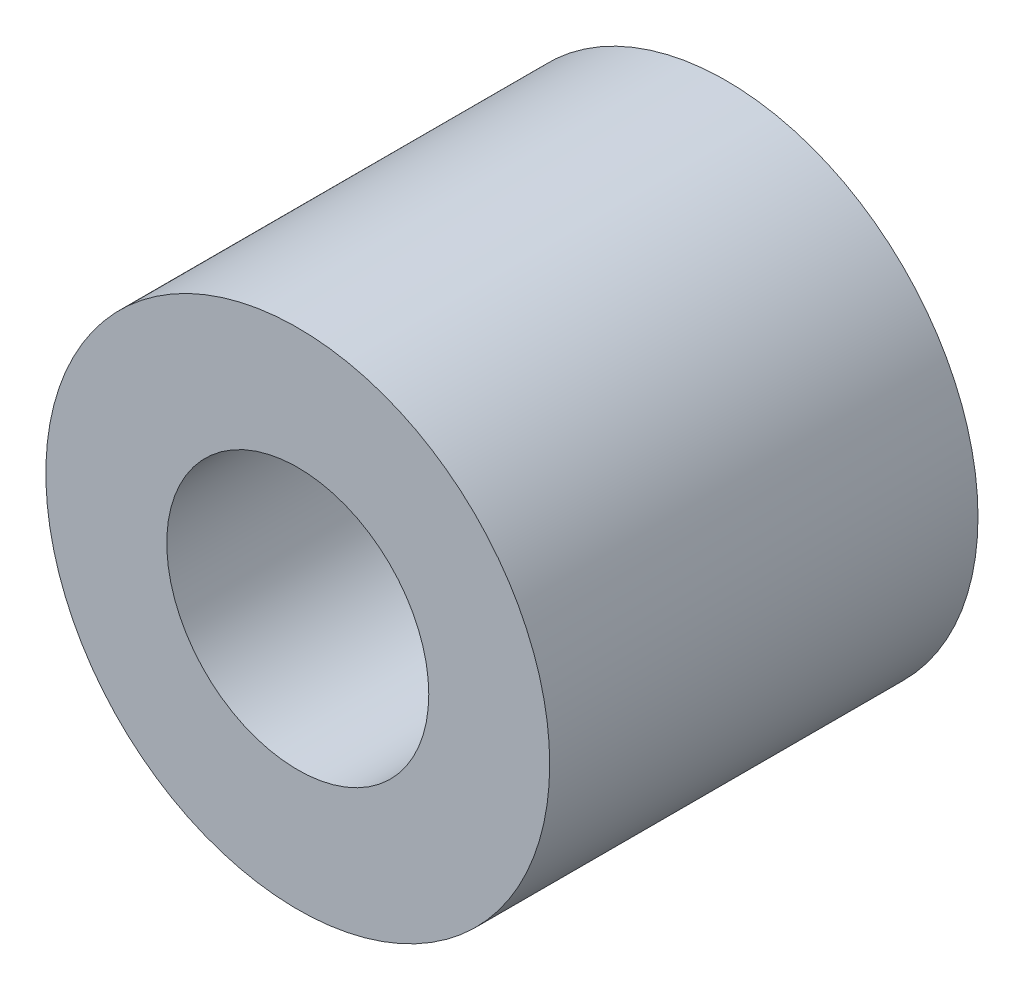
SolidWorks part; units mm, degrees
ref_plane "前视基准面" through (0, 0, 0) normal (0, 0, 1) x (1, 0, 0)
ref_plane "上视基准面" through (0, 0, 0) normal (0, 1, 0) x (1, 0, 0)
ref_plane "右视基准面" through (0, 0, 0) normal (1, 0, 0) x (0, 0, -1)
sketch "草图1" plane through (0, 0, 0) normal (0, 0, 1) x (1, 0, 0)
  circle A0 centre (0, 0) radius 2.6
  circle A1 centre (0, 0) radius 5
  dimension "D1" = 5.2
  dimension "D2" = 10
extrude "凸台-拉伸1" add sketch "草图1" along normal blind 8.5
